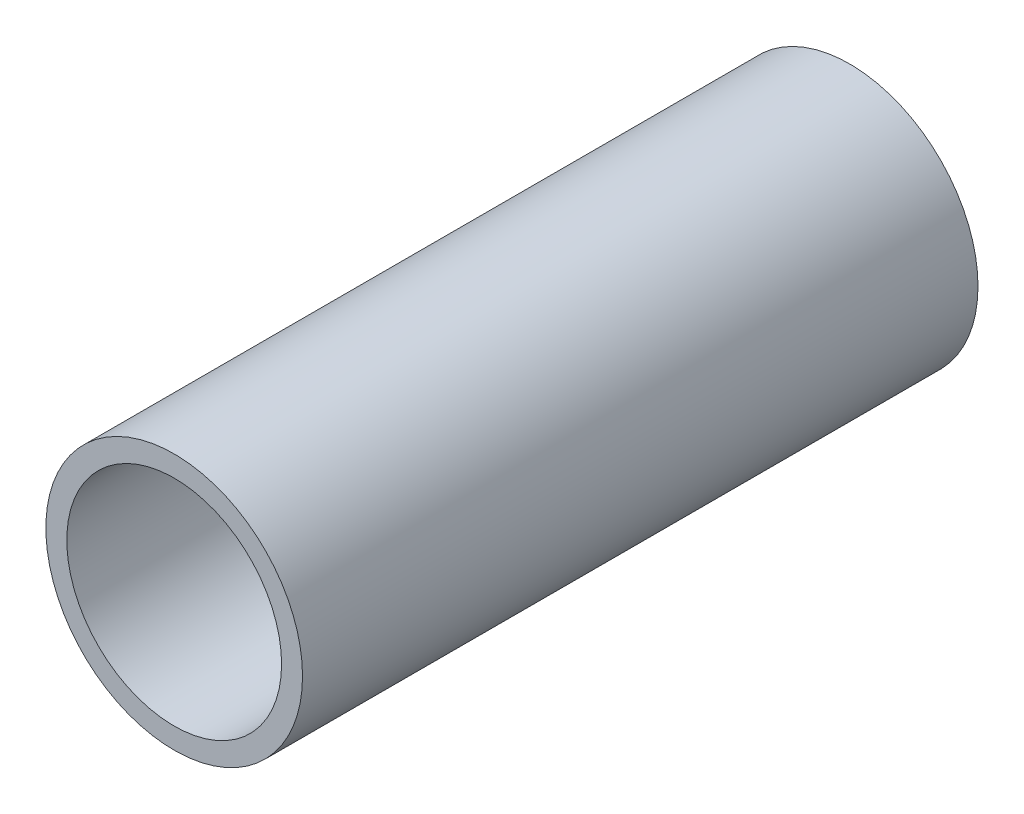
SolidWorks part; units mm, degrees
ref_plane "Front Plane" through (0, 0, 0) normal (0, 0, 1) x (1, 0, 0)
ref_plane "Top Plane" through (0, 0, 0) normal (0, 1, 0) x (1, 0, 0)
ref_plane "Right Plane" through (0, 0, 0) normal (1, 0, 0) x (0, 0, -1)
sketch "Sketch1" plane through (0, 0, 0) normal (0, 0, 1) x (1, 0, 0)
  circle A0 centre (0, 0) radius 24.13
  circle A1 centre (0, 0) radius 20.193
  dimension "D1" = 48.26
  dimension "D2" = 40.386
extrude "Boss-Extrude1" add sketch "Sketch1" along normal blind 127
